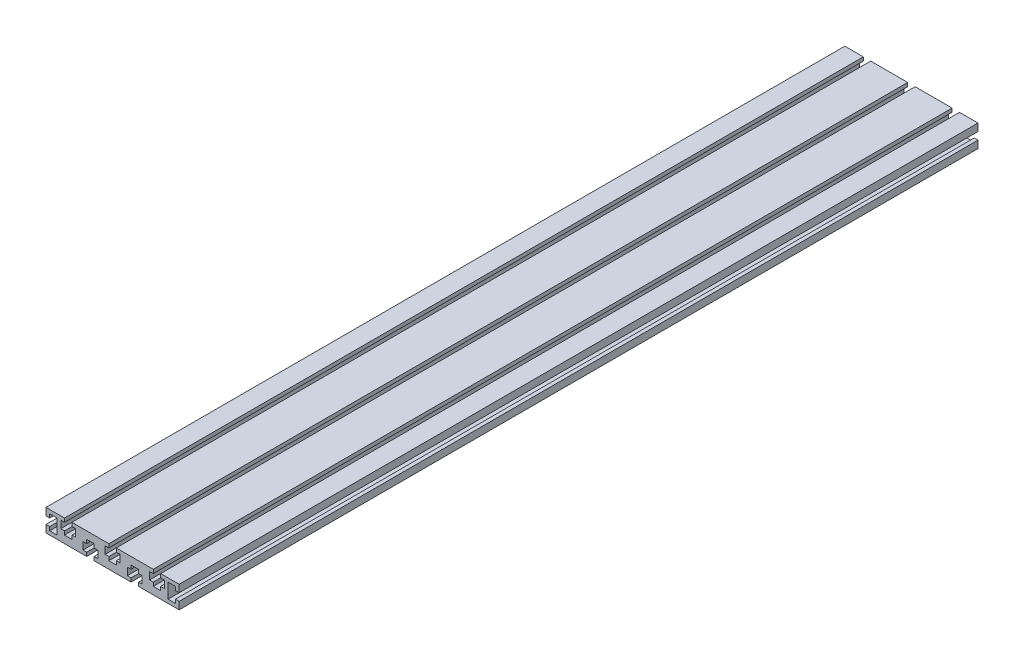
SolidWorks part; units mm, degrees
material "6063-O, Extruded Rod (SS)"
ref_plane "Front Plane" through (0, 0, 0) normal (0, 0, 1) x (1, 0, 0)
ref_plane "Top Plane" through (0, 0, 0) normal (0, 1, 0) x (1, 0, 0)
ref_plane "Right Plane" through (0, 0, 0) normal (1, 0, 0) x (0, 0, -1)
sketch "Sketch1" plane through (0, 0, 0) normal (0, 0, 1) x (1, 0, 0)
  line L0 (0, 20.2247) -> (0, -19.2716) construction
  line L1 (-45, -7.5) -> (-17.5, -7.5)
  line L2 (-45, -7.5) -> (-45, -2.5)
  line L3 (-45, 7.5) -> (-32.5, 7.5)
  line L4 (45, -7.5) -> (45, -2.5)
  line L5 (-45, -7.5) -> (45, 7.5) construction
  line L6 (-45, 7.5) -> (45, -7.5) construction
  line L7 (15, 20.2247) -> (15, -19.2716) construction
  line L8 (30, -19.2716) -> (30, 20.2247) construction
  line L9 (-15, 20.2247) -> (-15, -19.2716) construction
  line L10 (-30, -19.2716) -> (-30, 20.2247) construction
  line L11 (-2.5, 7.5) -> (-2.5, 5)
  line L12 (-2.5, 5) -> (-5, 5)
  line L13 (-5, 5) -> (-5, 0)
  line L14 (-5, 0) -> (-2.5, 0)
  line L15 (-2.5, 0) -> (-2.5, -2.5)
  line L16 (-2.5, -2.5) -> (2.5, -2.5)
  line L17 (2.5, -2.5) -> (2.5, 0)
  line L18 (2.5, 0) -> (5, 0)
  line L19 (5, 0) -> (5, 5)
  line L20 (5, 5) -> (2.5, 5)
  line L21 (2.5, 5) -> (2.5, 7.5)
  line L22 (2.5, 7.5) -> (27.5, 7.5)
  line L23 (35, 5) -> (32.5, 5)
  line L24 (27.5, -2.5) -> (32.5, -2.5)
  line L25 (32.5, 0) -> (35, 0)
  line L26 (32.5, 5) -> (32.5, 7.5)
  line L27 (27.5, 5) -> (25, 5)
  line L28 (32.5, -2.5) -> (32.5, 0)
  line L29 (25, 0) -> (27.5, 0)
  line L30 (27.5, 0) -> (27.5, -2.5)
  line L31 (25, 5) -> (25, 0)
  line L32 (27.5, 7.5) -> (27.5, 5)
  line L33 (35, 0) -> (35, 5)
  line L34 (-35, 0) -> (-32.5, 0)
  line L35 (-27.5, -2.5) -> (-27.5, 0)
  line L36 (-25, 5) -> (-27.5, 5)
  line L37 (-32.5, -2.5) -> (-27.5, -2.5)
  line L38 (-27.5, 0) -> (-25, 0)
  line L39 (-35, 5) -> (-35, 0)
  line L40 (-27.5, 5) -> (-27.5, 7.5)
  line L41 (-32.5, 5) -> (-35, 5)
  line L42 (-32.5, 0) -> (-32.5, -2.5)
  line L43 (-25, 0) -> (-25, 5)
  line L44 (-32.5, 7.5) -> (-32.5, 5)
  line L45 (-27.5, 7.5) -> (-2.5, 7.5)
  line L46 (32.5, 7.5) -> (45, 7.5)
  line L47 (-20, -5) -> (-17.5, -5)
  line L48 (-20, 0) -> (-20, -5)
  line L49 (-17.5, -5) -> (-17.5, -7.5)
  line L50 (-12.5, -5) -> (-10, -5)
  line L51 (-17.5, 2.5) -> (-12.5, 2.5)
  line L52 (-12.5, 0) -> (-12.5, 2.5)
  line L53 (-10, -5) -> (-10, 0)
  line L54 (-10, 0) -> (-12.5, 0)
  line L55 (-17.5, 2.5) -> (-17.5, 0)
  line L56 (-17.5, 0) -> (-20, 0)
  line L57 (-12.5, -7.5) -> (-12.5, -5)
  line L58 (-12.5, -7.5) -> (12.5, -7.5)
  line L59 (12.5, 0) -> (10, 0)
  line L60 (12.5, -5) -> (12.5, -7.5)
  line L61 (20, 0) -> (17.5, 0)
  line L62 (17.5, 0) -> (17.5, 2.5)
  line L63 (20, -5) -> (20, 0)
  line L64 (12.5, 2.5) -> (17.5, 2.5)
  line L65 (17.5, -7.5) -> (17.5, -5)
  line L66 (10, -5) -> (12.5, -5)
  line L67 (10, 0) -> (10, -5)
  line L68 (12.5, 2.5) -> (12.5, 0)
  line L69 (17.5, -5) -> (20, -5)
  line L70 (17.5, -7.5) -> (45, -7.5)
  line L71 (45, 2.5) -> (42.5, 2.5)
  line L72 (42.5, 2.5) -> (42.5, 5)
  line L73 (42.5, 5) -> (37.5, 5)
  line L74 (37.5, 5) -> (37.5, -5)
  line L75 (37.5, -5) -> (42.5, -5)
  line L76 (42.5, -5) -> (42.5, -2.5)
  line L77 (42.5, -2.5) -> (45, -2.5)
  line L78 (45, 2.5) -> (45, 7.5)
  line L79 (-42.5, 2.5) -> (-45, 2.5)
  line L80 (-45, -2.5) -> (-42.5, -2.5)
  line L81 (-37.5, 5) -> (-42.5, 5)
  line L82 (-42.5, 5) -> (-42.5, 2.5)
  line L83 (-42.5, -5) -> (-37.5, -5)
  line L84 (-37.5, -5) -> (-37.5, 5)
  line L85 (-42.5, -5) -> (-42.5, -2.5)
  line L86 (-45, 2.5) -> (-45, 7.5)
  point P0 (0, 0)
  dimension "D1" = 15
  dimension "D2" = 30
  dimension "D3" = 30
  dimension "D4" = 30
  dimension "D5" = 2.5
  dimension "D6" = 2.5
  dimension "D7" = 2.5
  dimension "D8" = 5
  dimension "D9" = 2.5
  dimension "D10" = 2.5
  dimension "D11" = 2.5
  dimension "D12" = 2.5
  dimension "D13" = 2.5
  dimension "D14" = 5
  dimension "D15" = 2.5
  dimension "D16" = 5
  dimension "D17" = 5
  dimension "D18" = 2.5
  dimension "D19" = 2.5
  dimension "D20" = 5
  dimension "D21" = 2.5
  dimension "D22" = 2.5
extrude "Boss-Extrude1" add sketch "Sketch1" along normal blind 540
